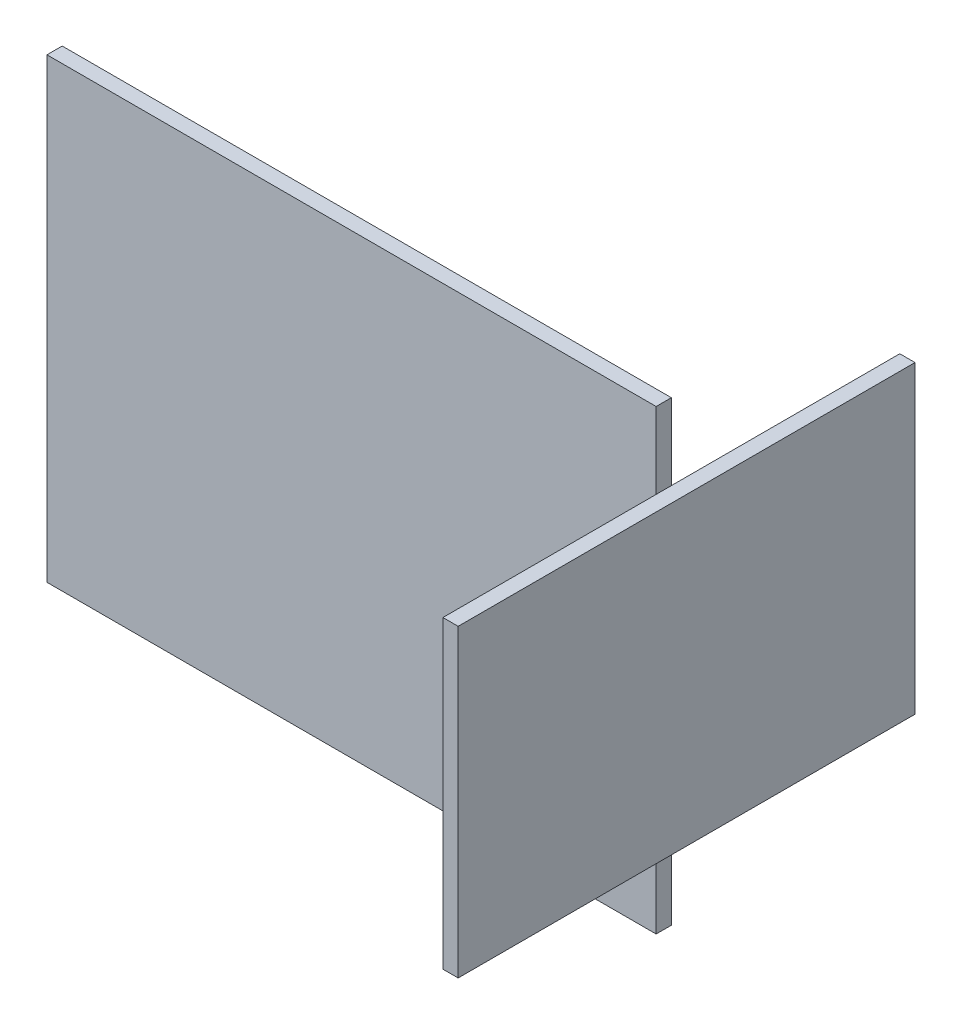
SolidWorks part; units mm, degrees
ref_plane "前视基准面" through (0, 0, 0) normal (0, 0, 1) x (1, 0, 0)
ref_plane "上视基准面" through (0, 0, 0) normal (0, 1, 0) x (1, 0, 0)
ref_plane "右视基准面" through (0, 0, 0) normal (1, 0, 0) x (0, 0, -1)
sketch "草图2" plane through (0, 0, 0) normal (0, 0, 1) x (1, 0, 0)
  line L1 (-40, 30) -> (40, 30)
  line L2 (-40, 30) -> (-40, -30)
  line L3 (-40, -30) -> (40, -30)
  line L4 (40, 30) -> (40, -30)
extrude "凸台-拉伸1" add sketch "草图2" along normal blind 2
sketch "草图3" plane through (40, 0, 0) normal (1, 0, 0) x (0, 0, -1)
  line L1 (-30, 20) -> (30, 20)
  line L2 (-30, 20) -> (-30, -20)
  line L3 (-30, -20) -> (30, -20)
  line L4 (30, 20) -> (30, -20)
extrude "凸台-拉伸2" add sketch "草图3" along normal blind 2
